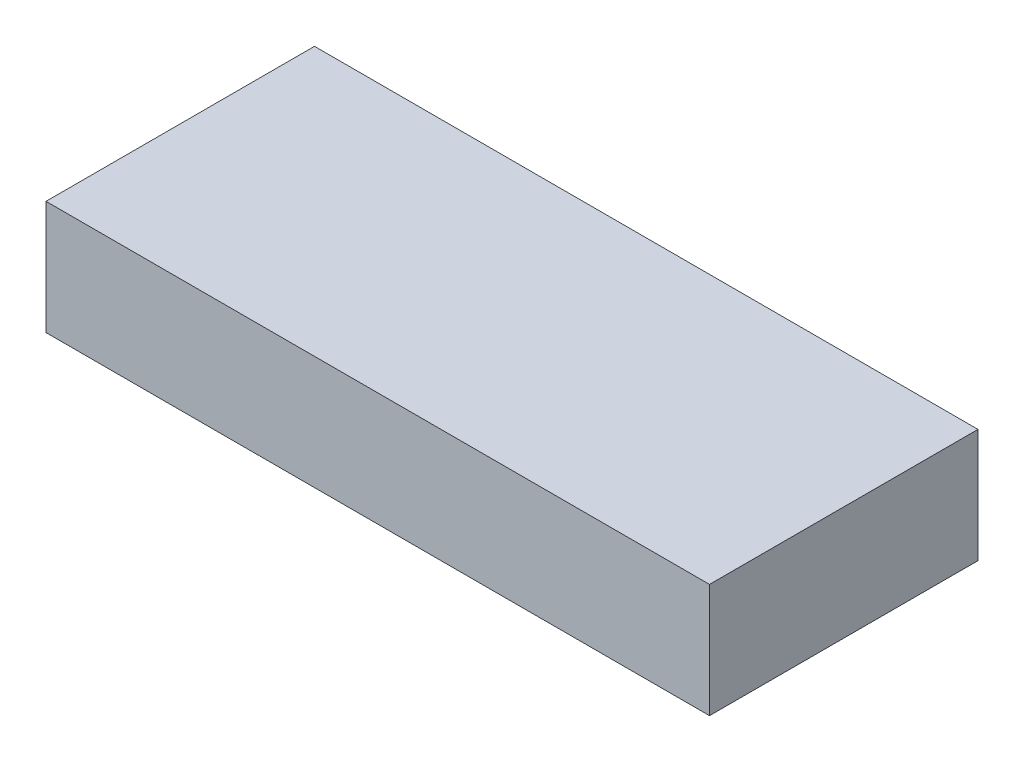
SolidWorks part; units mm, degrees
ref_plane "Front Plane" through (0, 0, 0) normal (0, 0, 1) x (1, 0, 0)
ref_plane "Top Plane" through (0, 0, 0) normal (0, 1, 0) x (1, 0, 0)
ref_plane "Right Plane" through (0, 0, 0) normal (1, 0, 0) x (0, 0, -1)
sketch "Sketch1" plane through (0, 0, 0) normal (0, 1, 0) x (1, 0, 0)
  line L1 (31.075, -12.575) -> (-31.075, -12.575)
  line L2 (31.075, -12.575) -> (31.075, 12.575)
  line L3 (31.075, 12.575) -> (-31.075, 12.575)
  line L4 (-31.075, -12.575) -> (-31.075, 12.575)
  line L5 (31.075, -12.575) -> (-31.075, 12.575) construction
  line L6 (31.075, 12.575) -> (-31.075, -12.575) construction
  point P0 (0, 0)
  dimension "D1" = 25.15
  dimension "D2" = 62.15
extrude "Boss-Extrude1" add sketch "Sketch1" along normal blind 10.65
